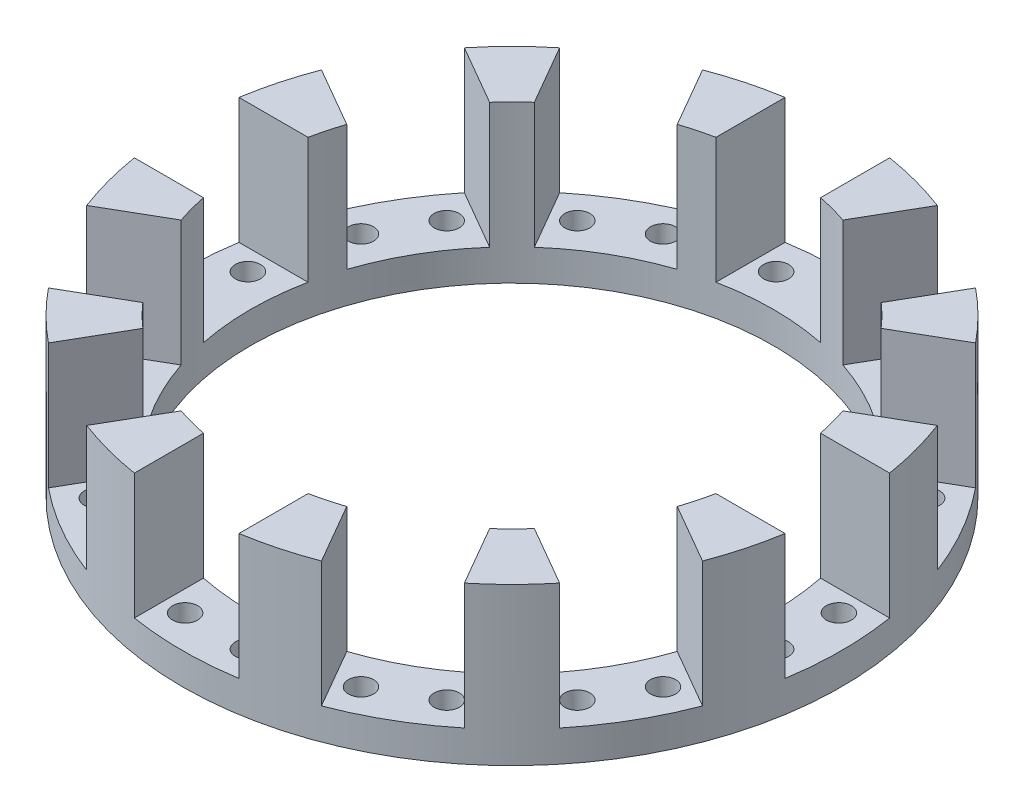
SolidWorks part; units mm, degrees
ref_plane "Front Plane" through (0, 0, 0) normal (0, 0, 1) x (1, 0, 0)
ref_plane "Top Plane" through (0, 0, 0) normal (0, 1, 0) x (1, 0, 0)
ref_plane "Right Plane" through (0, 0, 0) normal (1, 0, 0) x (0, 0, -1)
sketch "Sketch1" plane through (0, 0, 0) normal (0, 1, 0) x (1, 0, 0)
  circle A0 centre (0, 0) radius 125
  circle A1 centre (0, 0) radius 157.5
  dimension "D1" = 315
  dimension "D2" = 250
extrude "Boss-Extrude1" add sketch "Sketch1" along normal mid plane 75
sketch "Sketch2" plane through (0, 0, 0) normal (0, 0, 1) x (1, 0, 0)
  line L0 (-157.5, -37.5) -> (157.5, -37.5) construction
  line L1 (-25, -22.5) -> (25, -22.5)
  line L2 (-25, -22.5) -> (-25, 37.5)
  line L3 (-25, 37.5) -> (25, 37.5)
  line L4 (25, -22.5) -> (25, 37.5)
  line L5 (-25, -22.5) -> (25, 37.5) construction
  line L6 (-25, 37.5) -> (25, -22.5) construction
  point P0 (0, 7.5)
  dimension "D1" = 45
  dimension "D2" = 60
  dimension "D3" = 50
extrude "Cut-Extrude1" cut sketch "Sketch2" against normal through all both and the other way through all
pattern_circular "CirPattern1" count 12 over 360 about axis through (0, 0, 0) along (0, 1, 0) of "Cut-Extrude1"
sketch "Sketch3" plane through (0, -37.5, 0) normal (0, -1, 0) x (1, 0, 0)
  line L0 (0, -1000) -> (0, 49000) construction
  line L1 (-1000, 0) -> (49000, 0)
  circle A0 centre (-15, 141.25) radius 6
  circle A1 centre (15, 141.25) radius 6
  circle A2 centre (0, 0) radius 125 construction
  point P14 (0, 125)
  dimension "D1" = 12
  dimension "D2" = 12
  dimension "D3" = 30
  dimension "D4" = 16.25
  dimension "D5" = 142.0442
extrude "Cut-Extrude2" cut sketch "Sketch3" against normal through all
pattern_circular "CirPattern2" count 12 over 360 about axis through (0, 0, 0) along (0, 1, 0) of "Cut-Extrude2"
